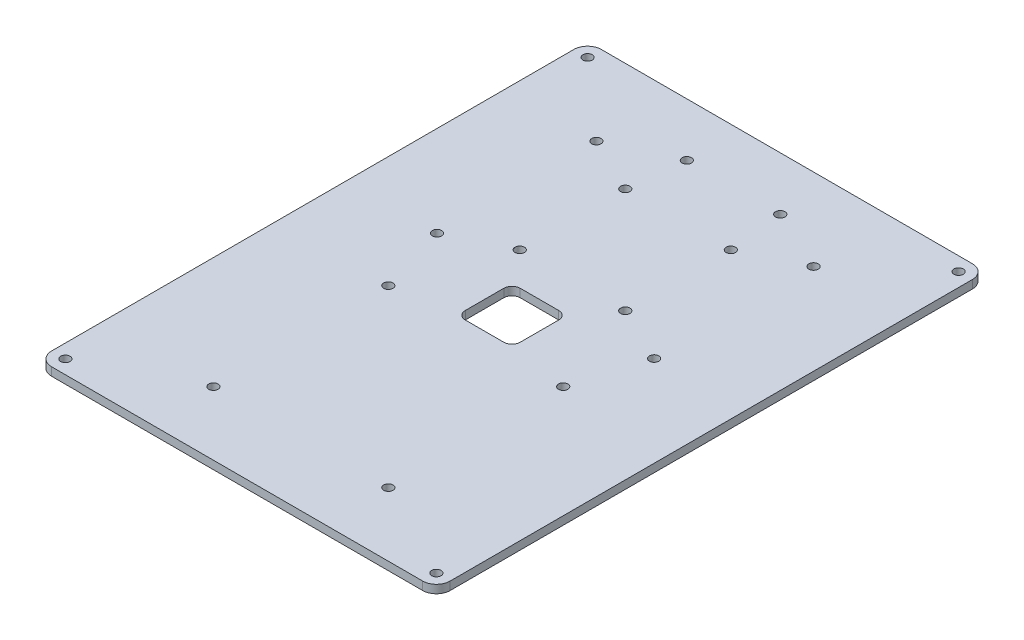
SolidWorks part; units mm, degrees
ref_plane "前视基准面" through (0, 0, 0) normal (0, 0, 1) x (1, 0, 0)
ref_plane "上视基准面" through (0, 0, 0) normal (0, 1, 0) x (1, 0, 0)
ref_plane "右视基准面" through (0, 0, 0) normal (1, 0, 0) x (0, 0, -1)
other "Configuration Table"
sketch "草图1" plane through (0, 0, 0) normal (0, 1, 0) x (1, 0, 0)
  line L0 (-31.8198, -13.1802) -> (0, -45) construction
  line L1 (-67.5, -100) -> (67.5, -100)
  line L2 (-72.5, -95) -> (-72.5, 95)
  line L3 (-67.5, 100) -> (67.5, 100)
  line L4 (72.5, -95) -> (72.5, 95)
  line L5 (-72.5, -100) -> (72.5, 100) construction
  line L6 (-72.5, 100) -> (72.5, -100) construction
  line L7 (-7, 10) -> (7, 10)
  line L8 (-10, 7) -> (-10, -7)
  line L9 (-7, -10) -> (7, -10)
  line L10 (10, 7) -> (10, -7)
  line L11 (-10, 10) -> (10, -10) construction
  line L12 (-10, -10) -> (10, 10) construction
  line L13 (-39.5, 70.2154) -> (39.5, 70.2154) construction
  line L14 (-39.5, 70.2154) -> (-39.5, 12.2154) construction
  line L15 (-39.5, 12.2154) -> (39.5, 12.2154) construction
  line L16 (39.5, 70.2154) -> (39.5, 12.2154) construction
  line L17 (-39.5, 70.2154) -> (39.5, 12.2154) construction
  line L18 (-39.5, 12.2154) -> (39.5, 70.2154) construction
  line L19 (-20, 88.11) -> (20, 88.11) construction
  line L20 (-20, 88.11) -> (-20, 73.11) construction
  line L21 (-20, 73.11) -> (20, 73.11) construction
  line L22 (20, 88.11) -> (20, 73.11) construction
  line L23 (-20, 88.11) -> (20, 73.11) construction
  line L24 (-20, 73.11) -> (20, 88.11) construction
  line L26 (-19.2, 22.0154) -> (19.2, 22.0154) construction
  line L27 (-19.2, 22.0154) -> (-19.2, 60.4154) construction
  line L28 (-19.2, 60.4154) -> (19.2, 60.4154) construction
  line L29 (19.2, 22.0154) -> (19.2, 60.4154) construction
  line L30 (-19.2, 22.0154) -> (19.2, 60.4154) construction
  line L31 (-19.2, 60.4154) -> (19.2, 22.0154) construction
  arc A0 (-67.5, 100) -> (-72.5, 95) centre (-67.5, 95) ccw
  arc A1 (72.5, 95) -> (67.5, 100) centre (67.5, 95) ccw
  arc A2 (67.5, -100) -> (72.5, -95) centre (67.5, -95) ccw
  arc A3 (-67.5, -100) -> (-72.5, -95) centre (-67.5, -95) cw
  circle A4 centre (-67.5, 95) radius 1.7
  circle A5 centre (67.5, 95) radius 1.7
  circle A6 centre (67.5, -95) radius 1.7
  circle A7 centre (-67.5, -95) radius 1.7
  arc A8 (-7, 10) -> (-10, 7) centre (-7, 7) ccw
  arc A9 (10, 7) -> (7, 10) centre (7, 7) ccw
  arc A10 (7, -10) -> (10, -7) centre (7, -7) ccw
  arc A11 (-10, -7) -> (-7, -10) centre (-7, -7) ccw
  circle A12 centre (-39.5, 70.2154) radius 1.7
  circle A13 centre (-39.5, 12.2154) radius 1.7
  circle A14 centre (39.5, 12.2154) radius 1.7
  circle A15 centre (39.5, 70.2154) radius 1.7
  circle A16 centre (-17, 80.61) radius 1.7
  circle A17 centre (17, 80.61) radius 1.7
  circle A18 centre (0, -45) radius 50 construction
  circle A19 centre (-31.8198, -13.1802) radius 1.7
  circle A20 centre (31.8198, -13.1802) radius 1.7
  circle A21 centre (31.8198, -76.8198) radius 1.7
  circle A22 centre (-31.8198, -76.8198) radius 1.7
  circle A23 centre (-19.2, 60.4154) radius 1.7
  circle A24 centre (19.2, 60.4154) radius 1.7
  circle A25 centre (19.2, 22.0154) radius 1.7
  circle A26 centre (-19.2, 22.0154) radius 1.7
  point P0 (0, 0)
  point P19 (0, 0)
  point P42 (0, 41.2154)
  point P53 (0, 80.61)
  point P60 (0, 41.2154)
  point P73 (0, -45)
  point P86 (0, 41.2154)
  dimension "D3" = 5
  dimension "D4" = 5
  dimension "D5" = 5
  dimension "D6" = 5
  dimension "D7" = 2
  dimension "D10" = 3
  dimension "D11" = 3
  dimension "D12" = 3
  dimension "D13" = 3
  dimension "D16" = 15
  dimension "D18" = 3
  dimension "D20" = 55
  dimension "D21" = 4
  dimension "D23" = 4
  dimension "D1" = 145
  dimension "D2" = 200
  dimension "D9" = 20
  dimension "D14" = 79
  dimension "D15" = 58
  dimension "D17" = 40
  dimension "D19" = 3
  dimension "D22" = 38.4
  dimension "D8" = 2
extrude "凸台-拉伸1" add sketch "草图1" along normal blind 3 contours A3 L1 A2 L4 A1 L3 A0 L2 A18 L8 A8 L7 A9 L10 A15 A14 A13 A12 A7 A6 A5 A4 L19 L22 L21 L20 | L8 A18 L10 A10 L9 A11
